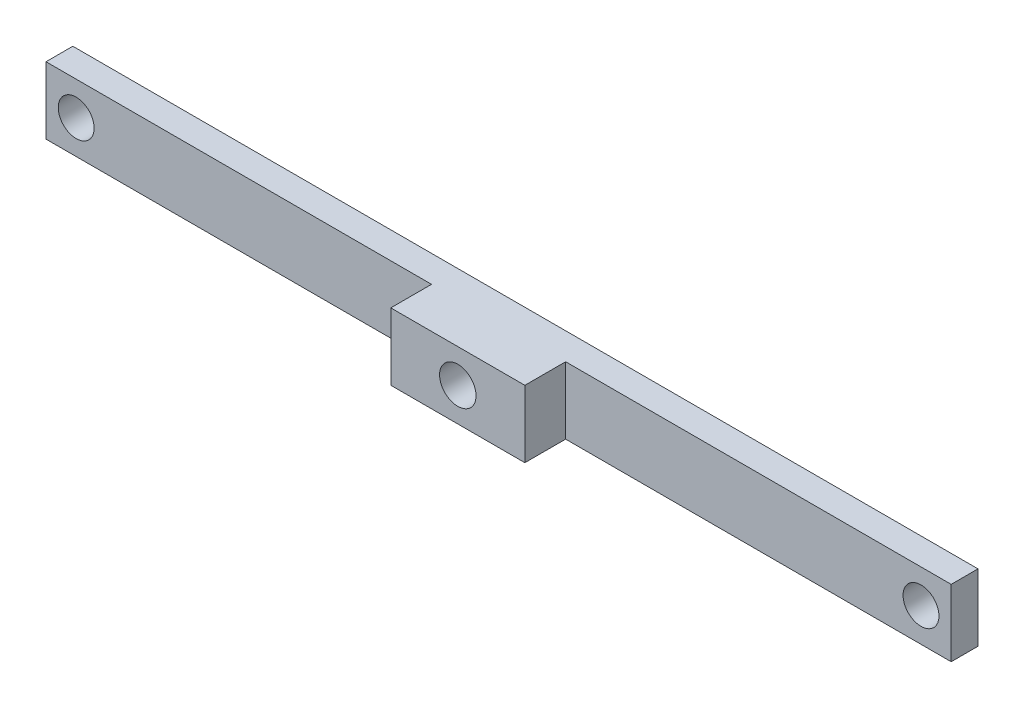
SolidWorks part; units mm, degrees
ref_plane "Front Plane" through (0, 0, 0) normal (0, 0, 1) x (1, 0, 0)
ref_plane "Top Plane" through (0, 0, 0) normal (0, 1, 0) x (1, 0, 0)
ref_plane "Right Plane" through (0, 0, 0) normal (1, 0, 0) x (0, 0, -1)
sketch "Sketch1" plane through (0, 0, 0) normal (0, 0, 1) x (1, 0, 0)
  line L1 (-42.8625, -3.175) -> (42.8625, -3.175)
  line L2 (-42.8625, -3.175) -> (-42.8625, 3.175)
  line L3 (-42.8625, 3.175) -> (42.8625, 3.175)
  line L4 (42.8625, -3.175) -> (42.8625, 3.175)
  line L5 (-42.8625, -3.175) -> (42.8625, 3.175) construction
  line L6 (-42.8625, 3.175) -> (42.8625, -3.175) construction
  point P0 (0, 0)
  dimension "D1" = 6.35
  dimension "D2" = 85.725
extrude "Boss-Extrude1" add sketch "Sketch1" along normal blind 6.4018
sketch "Sketch2" plane through (0, 0, 6.4018) normal (0, 0, 1) x (1, 0, 0)
  line L0 (-42.8625, -3.175) -> (42.8625, -3.175) construction
  line L1 (42.8625, 3.175) -> (6.35, 3.175)
  line L2 (42.8625, 3.175) -> (42.8625, -3.175)
  line L3 (42.8625, -3.175) -> (6.35, -3.175)
  line L4 (6.35, 3.175) -> (6.35, -3.175)
  dimension "D1" = 6.35
extrude "Cut-Extrude1" cut sketch "Sketch2" against normal offset from surface (3.8618 mm away) 2.54 up to face at (0, 0, 0)
sketch "Sketch3" plane through (0, 0, 2.54) normal (0, 0, 1) x (1, 0, 0)
  line L0 (0, 0) -> (36.83, 0) construction
  line L1 (36.83, 0) -> (40.005, 0) construction
  dimension "D1" = 36.83
  dimension "D2" = 40.005
hole_wizard "M3 Clearance Hole1" positions "Sketch5" profile "Sketch6" hole size "M3" standard "Ansi Metric" end condition through all
sketch "Sketch5" plane through (0, 0, 2.54) normal (0, 0, 1) x (1, 0, 0)
  point P4 (40.005, 0)
sketch "Sketch6" plane through (40.005, 0, 2.54) normal (1, 0, 0) x (0, -1, 0)
  line L0 (0, 0) -> (0, 2.54)
  line L1 (0, 2.54) -> (1.7, 2.54)
  line L2 (1.7, 2.54) -> (1.7, 0)
  line L5 (1.7, 0) -> (0, 0)
  line L11 (0, -6.35) -> (0, 107.95) construction
  dimension "Thru Hole Dia." = 3.4
  dimension "Thru Hole Depth" = 2.54
mirror "Mirror2" about plane through (0, 0, 0) normal (1, 0, 0) of "M3 Clearance Hole1", "Cut-Extrude1"
hole_wizard "#8-32 Tapped Hole1" positions "Sketch8" profile "Sketch9" tap size "#8-32" standard "Ansi Inch" end condition through all
sketch "Sketch8" plane through (0, 0, 6.4018) normal (0, 0, 1) x (1, 0, 0)
  point P1 (0, 0)
sketch "Sketch9" plane through (0, 0, 6.4018) normal (1, 0, 0) x (0, -1, 0)
  line L0 (0, 0) -> (0, 6.4018)
  line L1 (0, 6.4018) -> (1.7272, 6.4018)
  line L2 (1.7272, 6.4018) -> (1.7272, 0)
  line L5 (1.7272, 0) -> (0, 0)
  line L11 (0, -6.35) -> (0, 107.95) construction
  dimension "Thru Tap Drill Dia." = 3.4544
  dimension "Thru Tap Drill Depth" = 6.4018
cosmetic thread "Hole Thread1" parameters "D2"=4.1656
